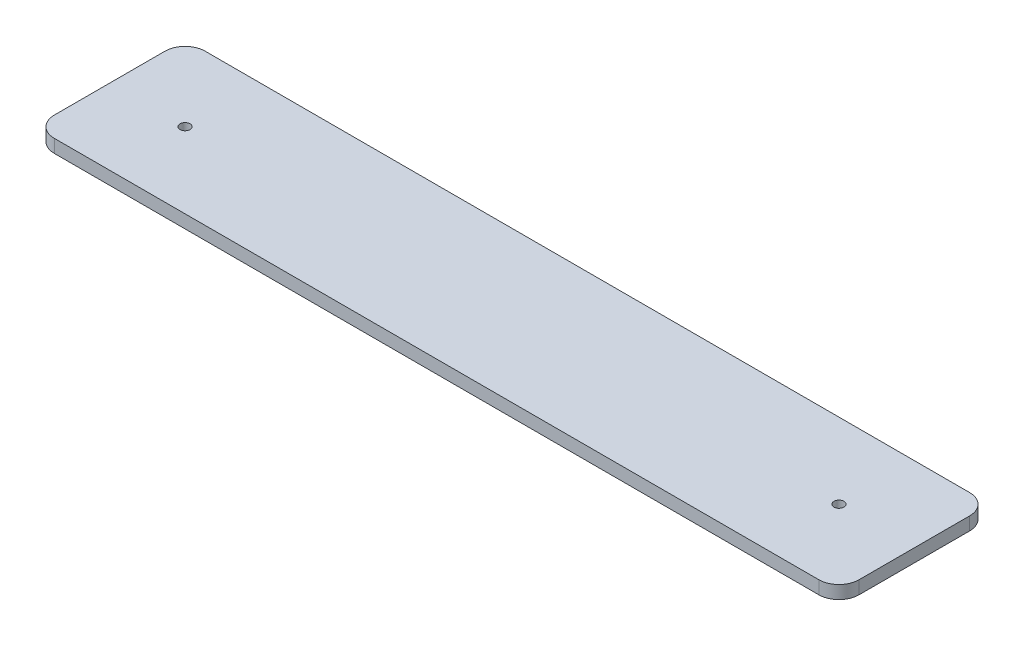
SolidWorks part; units mm, degrees
ref_plane "Front Plane" through (0, 0, 0) normal (0, 0, 1) x (1, 0, 0)
ref_plane "Top Plane" through (0, 0, 0) normal (0, 1, 0) x (1, 0, 0)
ref_plane "Right Plane" through (0, 0, 0) normal (1, 0, 0) x (0, 0, -1)
sketch "Sketch1" plane through (0, 0, 0) normal (0, 1, 0) x (1, 0, 0)
  line L1 (0, 0) -> (400, 0)
  line L2 (0, 0) -> (0, 75)
  line L3 (0, 75) -> (400, 75)
  line L4 (400, 0) -> (400, 75)
  dimension "D1" = 75
  dimension "D2" = 400
extrude "Boss-Extrude1" add sketch "Sketch1" along normal blind 6.5
fillet "Fillet1" radius 10 4 edges at (400, 3.25, -75) (400, 3.25, 0) (0, 3.25, 0) (0, 3.25, -75)
sketch "Sketch2" plane through (0, 6.5, 0) normal (0, 1, 0) x (1, 0, 0)
  line L0 (37.5, 37.5) -> (37.5, 75) construction
  line L1 (390, 75) -> (10, 75) construction
  line L2 (37.5, 37.5) -> (37.5, 0) construction
  line L3 (10, 0) -> (390, 0) construction
  line L4 (37.5, 37.5) -> (0, 37.5) construction
  line L5 (0, 65) -> (0, 10) construction
  line L6 (200, 75) -> (200, 0) construction
  circle A0 centre (37.5, 37.5) radius 2.5
  circle A1 centre (362.5, 37.5) radius 2.5
  dimension "D1" = 5
extrude "Cut-Extrude1" cut sketch "Sketch2" against normal up to next
